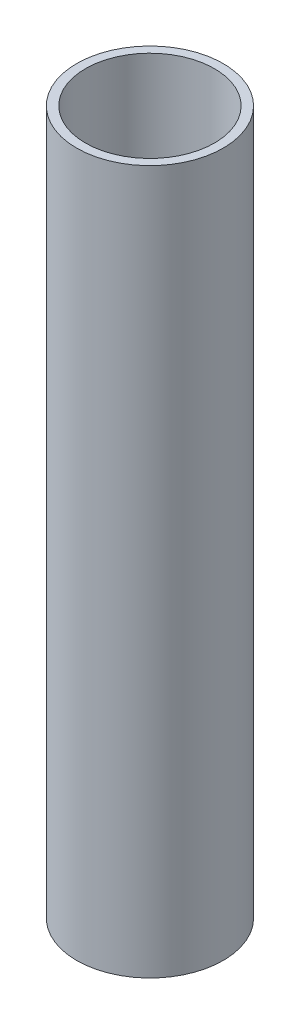
SolidWorks part; units mm, degrees
ref_plane "Front Plane" through (0, 0, 0) normal (0, 0, 1) x (1, 0, 0)
ref_plane "Top Plane" through (0, 0, 0) normal (0, 1, 0) x (1, 0, 0)
ref_plane "Right Plane" through (0, 0, 0) normal (1, 0, 0) x (0, 0, -1)
sketch "Sketch1" plane through (0, 0, 0) normal (0, 1, 0) x (1, 0, 0)
  circle A0 centre (0, 0) radius 12.5
  circle A1 centre (0, 0) radius 11
  dimension "D1" = 25
  dimension "D2" = 22
extrude "Boss-Extrude1" add sketch "Sketch1" along normal blind 120
